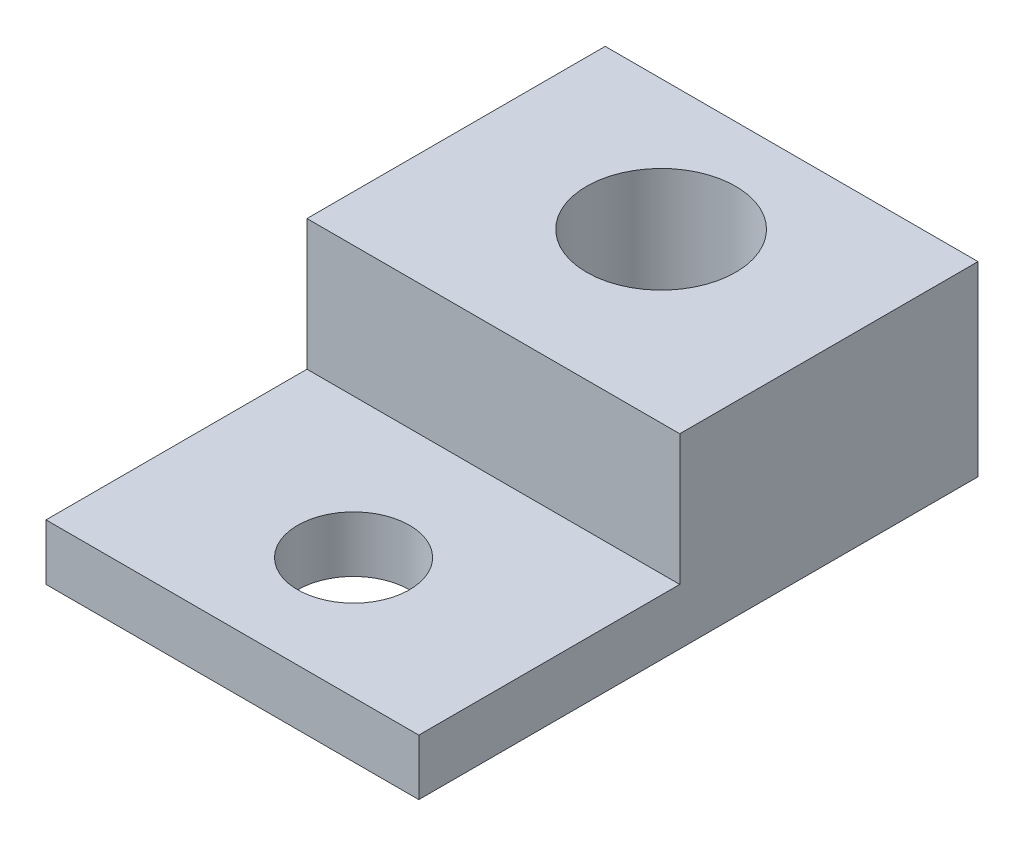
SolidWorks part; units mm, degrees
ref_plane "Front Plane" through (0, 0, 0) normal (0, 0, 1) x (1, 0, 0)
ref_plane "Top Plane" through (0, 0, 0) normal (0, 1, 0) x (1, 0, 0)
ref_plane "Right Plane" through (0, 0, 0) normal (1, 0, 0) x (0, 0, -1)
sketch "Sketch1" plane through (0, 0, 0) normal (0, 1, 0) x (1, 0, 0)
  line L1 (-10, -15) -> (10, -15)
  line L2 (-10, -15) -> (-10, 15)
  line L3 (-10, 15) -> (10, 15)
  line L4 (10, -15) -> (10, 15)
  line L5 (-10, -15) -> (10, 15) construction
  line L6 (-10, 15) -> (10, -15) construction
  point P0 (0, 0)
  dimension "D1" = 20
  dimension "D2" = 30
extrude "Boss-Extrude1" add sketch "Sketch1" along normal blind 3
sketch "Sketch2" plane through (0, 0, 0) normal (0, -1, 0) x (1, 0, 0)
  line L0 (10, -15) -> (-10, -15) construction
  line L1 (-2.5, -15) -> (2.5, -15)
  line L2 (-2.5, -15) -> (-2.5, -3)
  line L3 (-2.5, -3) -> (2.5, -3)
  line L4 (2.5, -15) -> (2.5, -3)
  line L5 (-2.5, -15) -> (2.5, -3) construction
  line L6 (-2.5, -3) -> (2.5, -15) construction
  point P0 (0, -9)
  dimension "D1" = 0
  dimension "D2" = 5
  dimension "D3" = 0
  dimension "D4" = 12
extrude "Boss-Extrude2" add sketch "Sketch2" along normal blind 3
sketch "Sketch3" plane through (0, 3, 0) normal (0, 1, 0) x (1, 0, 0)
  line L0 (10, 15) -> (-10, 15) construction
  circle A0 centre (0, 8) radius 4
  circle A1 centre (0, 8) radius 7
  dimension "D1" = 14
  dimension "D2" = 7
  dimension "D3" = 8
extrude "Boss-Extrude3" add sketch "Sketch3" along normal blind 7
sketch "Sketch4" plane through (0, 3, 0) normal (0, 1, 0) x (1, 0, 0)
  circle A1 centre (0, 8) radius 4
  circle A2 centre (0, 8) radius 4
  dimension "D1" = 0
extrude "Boss-Extrude4" add sketch "Sketch4" along normal blind 1
sketch "Sketch5" plane through (0, 3, 0) normal (0, 1, 0) x (1, 0, 0)
  line L0 (-10, -15) -> (10, -15) construction
  circle A0 centre (0, -8.5) radius 3
  point P4 (0, 0)
  point P7 (-0.7919, -3)
  dimension "D1" = 6
  dimension "D2" = 6.5
  dimension "D3" = 0
extrude "Cut-Extrude1" cut sketch "Sketch5" against normal through all both and the other way through all
chamfer "Chamfer1" [suppressed] distance 4 angle 45
sketch "Sketch6" plane through (0, 3, 0) normal (0, 1, 0) x (1, 0, 0)
  line L0 (10, -15) -> (10, 15) construction
  line L1 (-10, 15) -> (10, 15)
  line L2 (-10, 15) -> (-10, -1)
  line L3 (-10, -1) -> (10, -1)
  line L4 (10, 15) -> (10, -1)
  circle A0 centre (0, 8) radius 7 construction
  circle A1 centre (0, 8) radius 7
  circle A3 centre (0, 8) radius 4
  circle A4 centre (0, 8) radius 4
  line M6 (10, 15) -> (0, 15)
  circle M7 centre (0, 8) radius 7
  line M8 (0, 15) -> (-10, 15)
  line M9 (-10, 15) -> (-10, -15)
  line M11 (10, -15) -> (10, 15)
  dimension "D1" = 16
  dimension "D2" = 0
extrude "Boss-Extrude6" add sketch "Sketch6" along normal up to surface (7 mm away) contours A4 M7 | L3 M9 M11 M6 M7 M8 up to face at (0, 10, -1)
